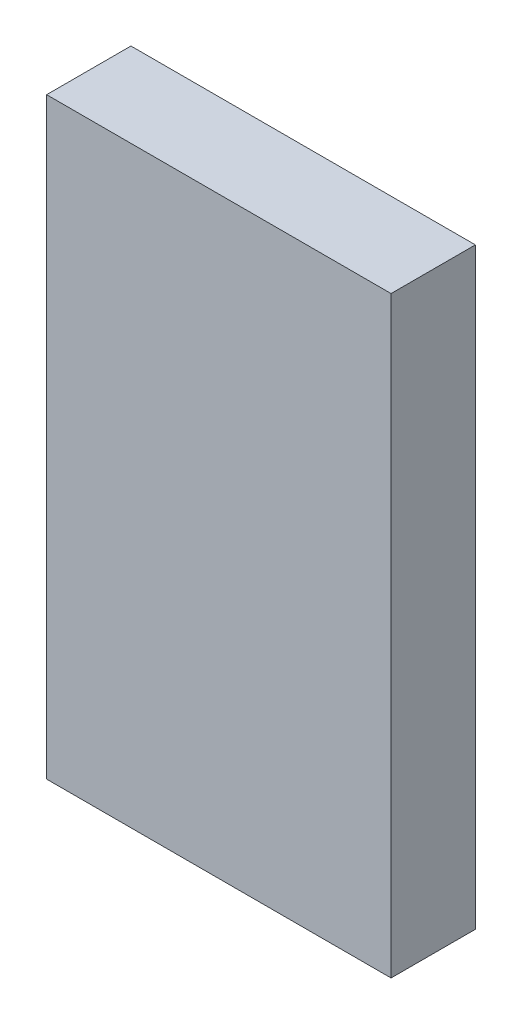
SolidWorks part; units mm, degrees
ref_plane "Front Plane" through (0, 0, 0) normal (0, 0, 1) x (1, 0, 0)
ref_plane "Top Plane" through (0, 0, 0) normal (0, 1, 0) x (1, 0, 0)
ref_plane "Right Plane" through (0, 0, 0) normal (1, 0, 0) x (0, 0, -1)
sketch "Sketch1" plane through (0, 0, 0) normal (0, 0, 1) x (1, 0, 0)
  line L1 (-40.85, -70.3) -> (40.85, -70.3)
  line L2 (-40.85, -70.3) -> (-40.85, 70.3)
  line L3 (-40.85, 70.3) -> (40.85, 70.3)
  line L4 (40.85, -70.3) -> (40.85, 70.3)
  line L5 (-40.85, -70.3) -> (40.85, 70.3) construction
  line L6 (-40.85, 70.3) -> (40.85, -70.3) construction
  point P0 (0, 0)
  dimension "D1" = 81.7
  dimension "D2" = 140.6
extrude "Boss-Extrude1" add sketch "Sketch1" along normal mid plane 20
